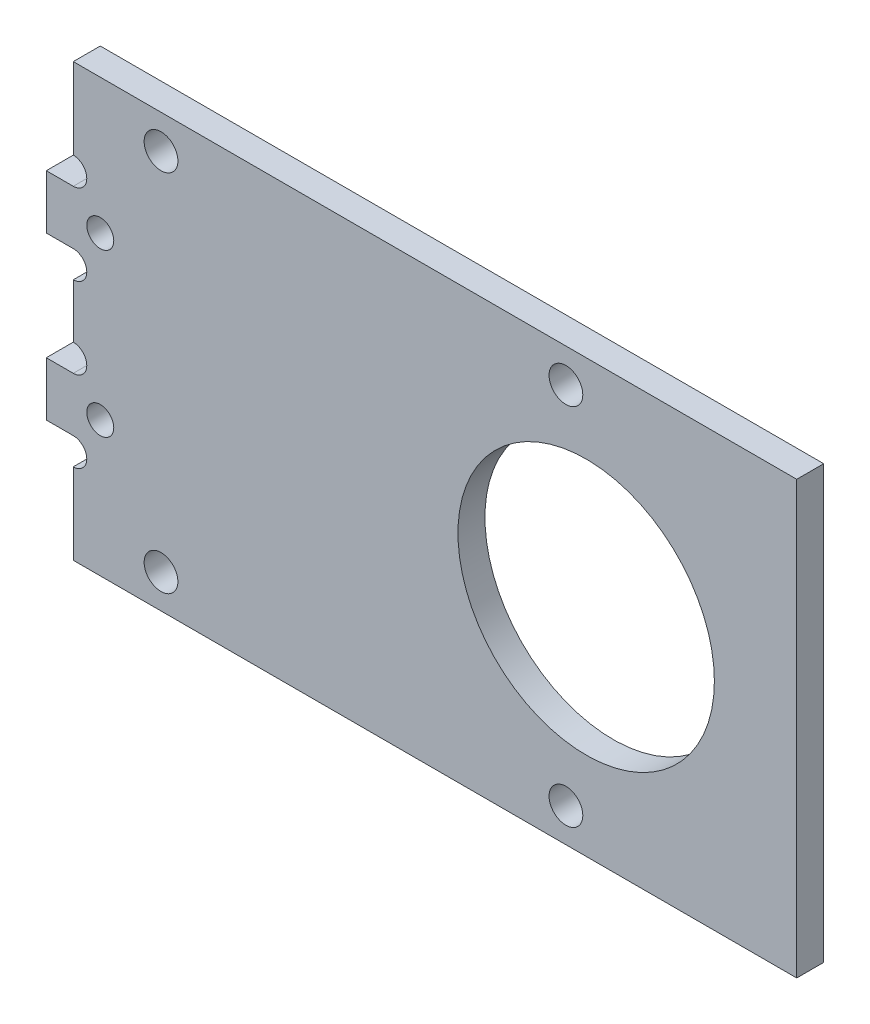
SolidWorks part; units mm, degrees
material "自訂玻璃纖維"
ref_plane "前基準面" through (0, 0, 0) normal (0, 0, 1) x (1, 0, 0)
ref_plane "上基準面" through (0, 0, 0) normal (0, 1, 0) x (1, 0, 0)
ref_plane "右基準面" through (0, 0, 0) normal (1, 0, 0) x (0, 0, -1)
sketch "草圖1" plane through (0, 0, 0) normal (0, 0, 1) x (1, 0, 0)
  line L0 (-8.8684, 14.8937) -> (-8.8684, 15.8937)
  line L1 (-7.8684, 15.8937) -> (43.7816, 15.8937)
  line L2 (-8.8684, 14.8937) -> (-8.8684, 9.8937)
  line L3 (-7.8684, -16.1063) -> (43.7816, -16.1063)
  line L4 (44.7316, 14.8937) -> (44.7316, -15.1063)
  line L5 (-8.8684, 15.8937) -> (-7.8684, 15.8937)
  line L6 (-8.8684, -15.1063) -> (-8.8684, -16.1063)
  line L7 (-8.8684, -16.1063) -> (-7.8684, -16.1063)
  line L8 (44.7316, 14.8937) -> (44.7316, 15.8937)
  line L9 (44.7316, 15.8937) -> (43.7816, 15.8937)
  line L10 (44.7316, -15.1063) -> (44.7316, -16.1063)
  line L11 (44.7316, -16.1063) -> (43.7816, -16.1063)
  line L12 (-8.8684, 1.8937) -> (-8.8684, -2.1063)
  line L13 (-8.8684, 7.8937) -> (-10.8684, 7.8937)
  line L14 (-10.8684, -4.1063) -> (-10.8684, -8.1063)
  line L15 (-8.8684, 3.8937) -> (-10.8684, 3.8937)
  line L16 (-10.8684, 7.8937) -> (-10.8684, 3.8937)
  line L17 (-8.8684, -8.1063) -> (-10.8684, -8.1063)
  line L18 (-8.8684, -4.1063) -> (-10.8684, -4.1063)
  line L19 (-8.8684, -10.1063) -> (-8.8684, -15.1063)
  arc A0 (-8.8684, 7.8937) -> (-8.8684, 9.8937) centre (-8.8684, 8.8937) ccw
  circle A1 centre (-6.8684, 5.8937) radius 1
  circle A2 centre (-6.8684, -6.1063) radius 1
  arc A3 (-8.8684, 3.8937) -> (-8.8684, 1.8937) centre (-8.8684, 2.8937) cw
  arc A4 (-8.8684, -4.1063) -> (-8.8684, -2.1063) centre (-8.8684, -3.1063) ccw
  arc A5 (-8.8684, -8.1063) -> (-8.8684, -10.1063) centre (-8.8684, -9.1063) cw
  circle A6 centre (-2.3684, 13.3937) radius 1.25
  circle A7 centre (-2.3684, -13.6063) radius 1.25
  circle A8 centre (27.6316, 13.3937) radius 1.25
  circle A9 centre (27.6316, -13.6063) radius 1.25
  circle A10 centre (29.1316, -0.1063) radius 9.5
  point P10 (-8.8684, -16.1063)
  point P15 (44.7316, 15.8937)
  point P18 (-8.8684, 15.8937)
  dimension "D2" = 53.6
  dimension "D3" = 2
  dimension "D4" = 4
  dimension "D5" = 12
  dimension "D7" = 2
  dimension "D13" = 2.5
  dimension "D15" = 19
  dimension "D17" = 27
  dimension "D18" = 2.5
  dimension "D19" = 30
  dimension "D20" = 1.5
  dimension "D6" = 2
  dimension "D1" = 32
extrude "填料-伸長1" add sketch "草圖1" along normal blind 2
